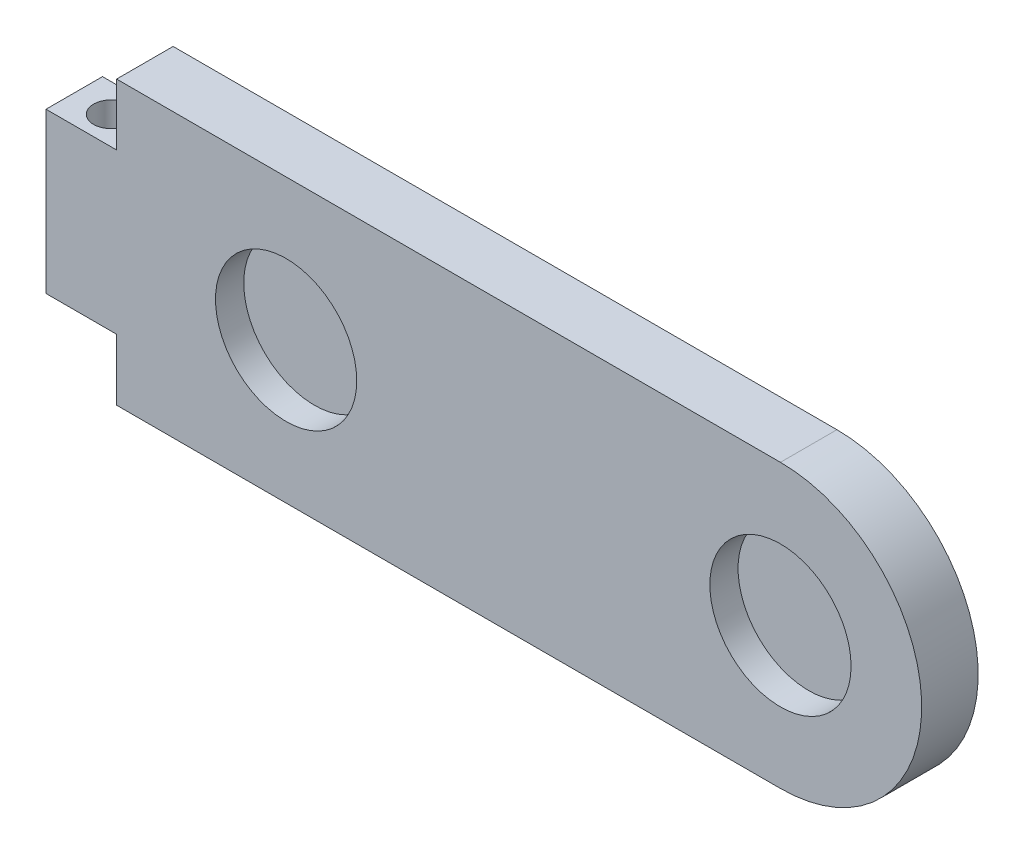
SolidWorks part; units mm, degrees
ref_plane "前视基准面" through (0, 0, 0) normal (0, 0, 1) x (1, 0, 0)
ref_plane "上视基准面" through (0, 0, 0) normal (0, 1, 0) x (1, 0, 0)
ref_plane "右视基准面" through (0, 0, 0) normal (1, 0, 0) x (0, 0, -1)
sketch "草图1" plane through (0, 0, 0) normal (0, 0, 1) x (1, 0, 0)
  line L0 (0, 0) -> (37, 0) construction
  line L1 (0, 10) -> (37, 10)
  line L2 (0, -10) -> (37, -10)
  line L3 (0, 10) -> (-10, 10)
  line L4 (-10, 10) -> (-10, -10)
  line L5 (-10, -10) -> (0, -10)
  arc A1 (37, -10) -> (37, 10) centre (37, 0) ccw
  point P3 (18.5, 0)
  dimension "D2" = 10
  dimension "D1" = 37
extrude "凸台-拉伸1" add sketch "草图1" along normal blind 4
sketch "草图2" plane through (-10, 0, 0) normal (-1, 0, 0) x (0, 0, 1)
  line L1 (0, 10) -> (4, 10)
  line L2 (0, 10) -> (0, -10)
  line L3 (0, -10) -> (4, -10)
  line L4 (4, 10) -> (4, -10)
extrude "凸台-拉伸2" add sketch "草图2" along normal blind 5
sketch "草图3" plane through (0, 0, 4) normal (0, 0, 1) x (1, 0, 0)
  line L0 (-15, 0) -> (0, 0) construction
  line L1 (-15, -10) -> (-15, 10) construction
  line L3 (-15, 10) -> (-10, 10)
  line L4 (-15, 10) -> (-15, 5.65)
  line L5 (-15, 5.65) -> (-10, 5.65)
  line L6 (-10, 10) -> (-10, 5.65)
  line L7 (-15, -10) -> (-10, -10)
  line L8 (-15, -10) -> (-15, -5.65)
  line L9 (-15, -5.65) -> (-10, -5.65)
  line L10 (-10, -10) -> (-10, -5.65)
  dimension "D1" = 4.35
  dimension "D2" = 4.35
  dimension "D3" = 5
  dimension "D4" = 5
extrude "切除-拉伸1" cut sketch "草图3" against normal up to surface (4 mm away) up to face at (13.5, 0, 0)
sketch "草图4" plane through (0, 5.65, 0) normal (0, 1, 0) x (1, 0, 0)
  line L0 (-15, -2) -> (0, -2) construction
  line L1 (-15, 0) -> (-15, -4) construction
  circle A0 centre (-12.3797, -2) radius 1.25
  dimension "D1" = 2.5
extrude "切除-拉伸2" cut sketch "草图4" against normal up to surface (11.3 mm away) up to face at (-12.5, -5.65, 2)
sketch "草图6" plane through (0, 0, 4) normal (0, 0, 1) x (1, 0, 0)
  circle A0 centre (37, 0) radius 5
  circle A1 centre (2, 0) radius 5
  dimension "D1" = 10
  dimension "D2" = 10
  dimension "D3" = 35
extrude "切除-拉伸4" cut sketch "草图6" against normal blind 2
